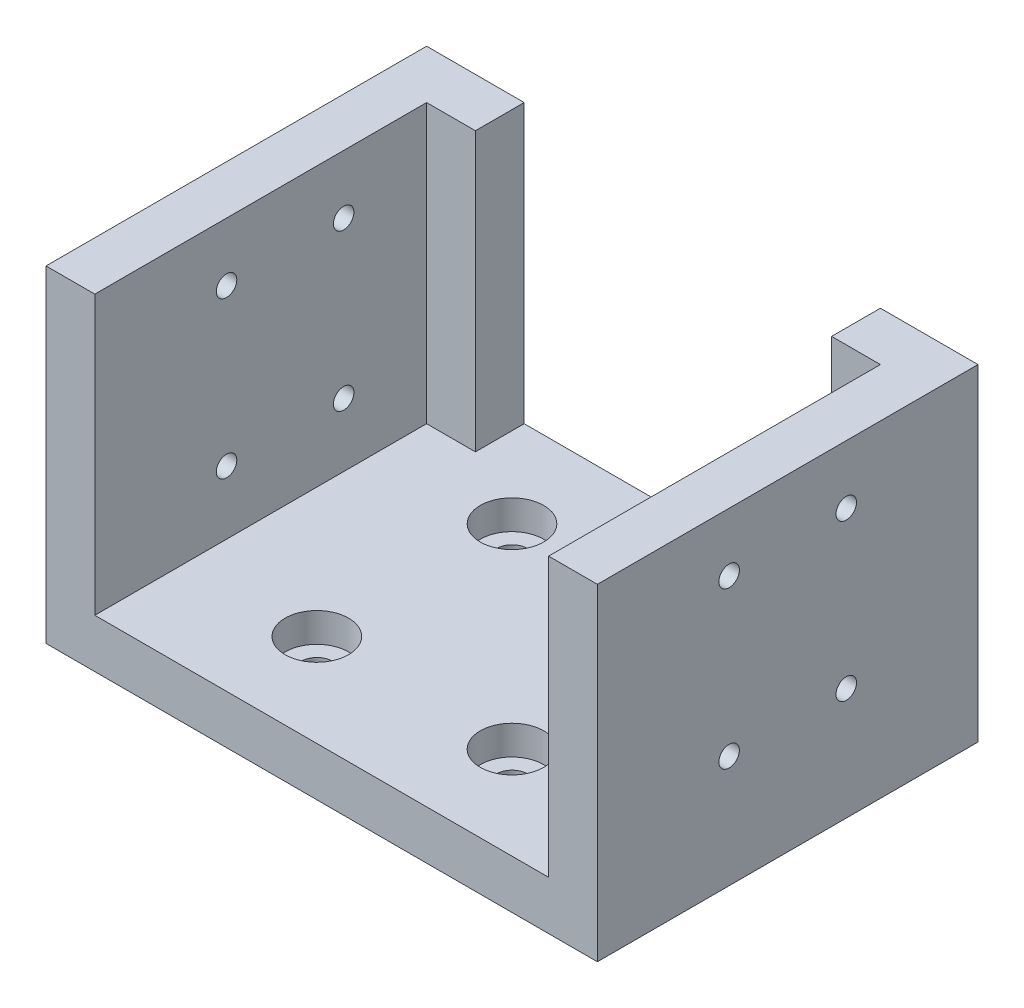
SolidWorks part; units mm, degrees
material "ABS"
ref_plane "Front Plane" through (0, 0, 0) normal (0, 0, 1) x (1, 0, 0)
ref_plane "Top Plane" through (0, 0, 0) normal (0, 1, 0) x (1, 0, 0)
ref_plane "Right Plane" through (0, 0, 0) normal (1, 0, 0) x (0, 0, -1)
sketch "Sketch9" plane through (0, 0, 0) normal (0, 1, 0) x (1, 0, 0)
  line L1 (-28.25, -19.5) -> (28.25, -19.5)
  line L2 (-28.25, -19.5) -> (-28.25, 19.5)
  line L3 (-28.25, 19.5) -> (28.25, 19.5)
  line L4 (28.25, -19.5) -> (28.25, 19.5)
  line L5 (-28.25, -19.5) -> (28.25, 19.5) construction
  line L6 (-28.25, 19.5) -> (28.25, -19.5) construction
  point P0 (0, 0)
  point P5 (0, 0)
  dimension "D1" = 56.5
  dimension "D2" = 39
extrude "Boss-Extrude7" add sketch "Sketch9" along normal blind 33.5 contours L2 L1 L4 L3
sketch "Sketch10" plane through (28.25, 0, 0) normal (1, 0, 0) x (0, 0, -1)
  line L0 (0, 33.5) -> (0, 0) construction
  line L1 (-19.5, 33.5) -> (19.5, 33.5) construction
  line L2 (-19.5, 19.5) -> (19.5, 19.5) construction
  line L3 (-19.5, 33.5) -> (-19.5, 0) construction
  line L4 (19.5, 33.5) -> (19.5, 0) construction
  line L5 (-19.5, 0) -> (19.5, 0) construction
  circle A0 centre (-6, 11.5) radius 1.05
  circle A1 centre (6, 11.5) radius 1.05
  circle A2 centre (6, 27.5) radius 1.05
  circle A3 centre (-6, 27.5) radius 1.05
  dimension "D2" = 8
  dimension "D1" = 19.5
  dimension "D3" = 6
extrude "Cut-Extrude2" cut sketch "Sketch10" against normal through all
sketch "Sketch11" plane through (0, 33.5, 0) normal (0, 1, 0) x (1, 0, 0)
  line L4 (-28.25, -19.5) -> (28.25, -19.5) construction
  line L6 (-23.25, -14.5) -> (-23.25, -19.5)
  line L7 (-23.25, -19.5) -> (23.25, -19.5)
  line L8 (23.25, 14.5) -> (-23.25, 14.5)
  line L9 (-23.25, 14.5) -> (-23.25, -14.5)
  line L10 (-23.25, -14.5) -> (23.25, -14.5)
  line L11 (23.25, -14.5) -> (23.25, 14.5)
  line L12 (23.25, 14.5) -> (-23.25, 14.5)
  line L13 (-23.25, 14.5) -> (-23.25, -14.5)
  line L15 (23.25, -14.5) -> (23.25, 14.5)
  line L16 (23.25, -14.5) -> (23.25, -19.5)
  dimension "D1" = 5
extrude "Cut-Extrude3" cut sketch "Sketch11" against normal blind 28.5
sketch "Sketch12" plane through (0, 0, -14.5) normal (0, 0, 1) x (1, 0, 0)
  line L0 (23.25, 33.5) -> (-23.25, 33.5) construction
  line L1 (-18.25, 33.5) -> (18.25, 33.5)
  line L2 (-18.25, 33.5) -> (-18.25, 5)
  line L3 (-18.25, 5) -> (18.25, 5)
  line L4 (18.25, 33.5) -> (18.25, 5)
  line L5 (-23.25, 5) -> (23.25, 5) construction
  line L6 (-23.25, 5) -> (-23.25, 33.5) construction
  line L7 (23.25, 5) -> (23.25, 33.5) construction
  dimension "D1" = 5
  dimension "D2" = 5
extrude "Cut-Extrude4" cut sketch "Sketch12" against normal through all
sketch "Sketch13" plane through (0, 5, 0) normal (0, 1, 0) x (1, 0, 0)
  line L0 (0, 0) -> (0, 21.1591) construction
  line L1 (0, 0) -> (11.6237, 0) construction
hole_wizard "CBORE for M3 Socket Head Cap Screw3" positions "3DSketch3" profile "Sketch20" counterbore size "M3" standard "IS" end condition through all
sketch3d "3DSketch3"
  line L0 (0, 5, 0) -> (0, 5, -21.1591) construction
  line L1 (0, 5, 0) -> (11.6237, 5, 0) construction
  point P0 (10, 5, -10)
  point P2 (10, 5, 10)
  point P4 (-10, 5, 10)
  point P6 (-10, 5, -10)
  dimension "D1" = 10
  dimension "D2" = 10
  dimension "D3" = 10
  dimension "D4" = 10
  dimension "D5" = 10
  dimension "D6" = 10
  dimension "D7" = 10
  dimension "D8" = 10
sketch "Sketch20" plane through (10, 5, -10) normal (1, 0, 0) x (0, 0, 1)
  line L0 (0, 0) -> (0, 5)
  line L1 (0, 5) -> (1.6, 5)
  line L3 (1.6, 5) -> (1.6, 3)
  line L4 (1.6, 3) -> (3.25, 3)
  line L5 (3.25, 3) -> (3.25, 0)
  line L7 (3.25, 0) -> (0, 0)
  line L11 (0, -6.35) -> (0, 107.95) construction
  dimension "Thru Hole Dia." = 3.2
  dimension "Thru Hole Depth" = 5
  dimension "C'Bore Dia." = 6.5
  dimension "C'Bore Depth" = 3
